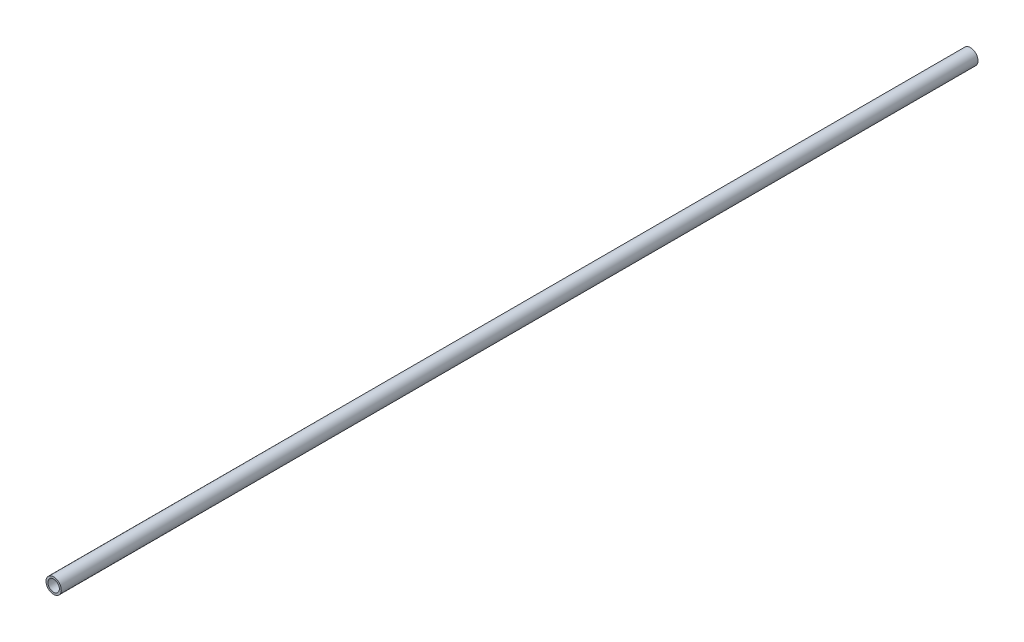
SolidWorks part; units mm, degrees
ref_plane "Front" through (0, 0, 0) normal (0, 0, 1) x (1, 0, 0)
ref_plane "Top" through (0, 0, 0) normal (0, 1, 0) x (1, 0, 0)
ref_plane "Right" through (0, 0, 0) normal (1, 0, 0) x (0, 0, -1)
sketch "Sketch1" plane through (0, 0, 0) normal (0, 0, 1) x (1, 0, 0)
  line L0 (0, 9.525) -> (0, 12.7) construction
  circle A0 centre (0, 0) radius 9.525
  circle A1 centre (0, 0) radius 12.7
  dimension "D1" = 25.4
  dimension "D2" = 3.175
extrude "Boss-Extrude1" add sketch "Sketch1" along normal blind 1524
